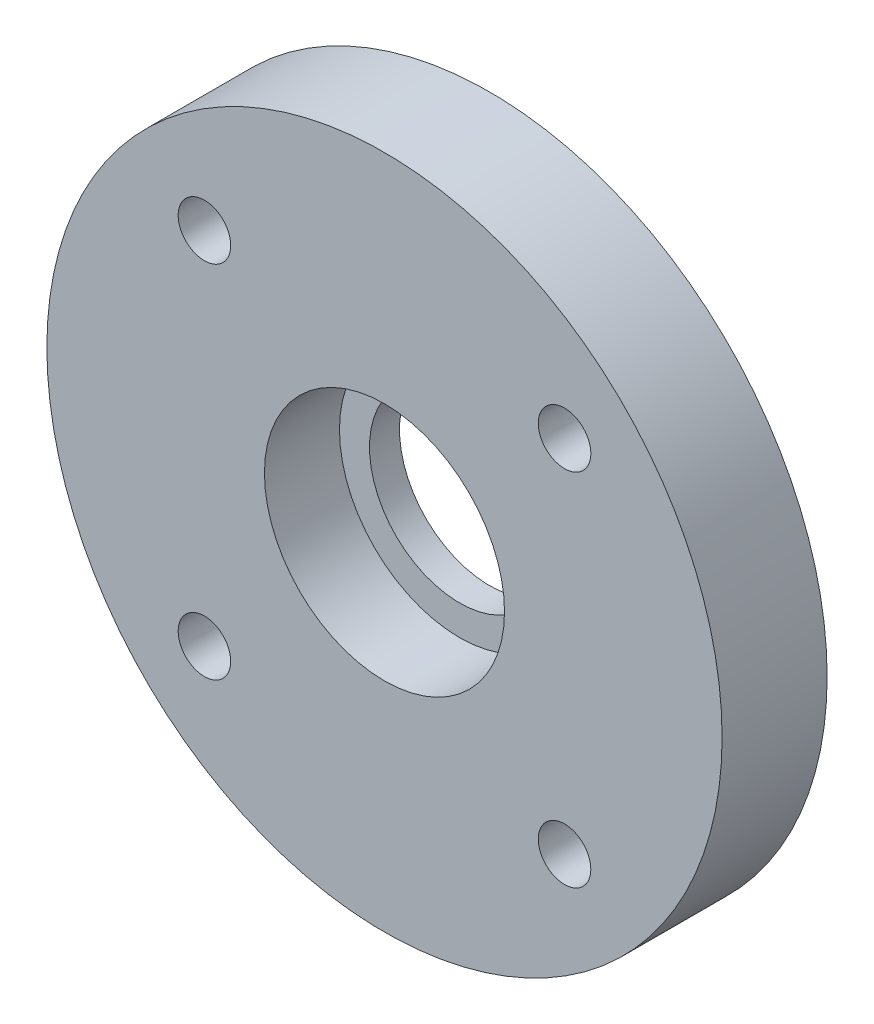
SolidWorks part; units mm, degrees
ref_plane "Front Plane" through (0, 0, 0) normal (0, 0, 1) x (1, 0, 0)
ref_plane "Top Plane" through (0, 0, 0) normal (0, 1, 0) x (1, 0, 0)
ref_plane "Right Plane" through (0, 0, 0) normal (1, 0, 0) x (0, 0, -1)
sketch "Sketch1" plane through (0, 0, 0) normal (0, 0, 1) x (1, 0, 0)
  circle A0 centre (0, 0) radius 22.5
  circle A1 centre (0, 0) radius 6
  dimension "D1" = 45
  dimension "D2" = 12
extrude "Boss-Extrude1" add sketch "Sketch1" along normal blind 7
sketch "Sketch2" plane through (0, 0, 7) normal (0, 0, 1) x (1, 0, 0)
  circle A0 centre (0, 0) radius 8
  dimension "D1" = 16
extrude "Cut-Extrude1" cut sketch "Sketch2" against normal blind 5
sketch "Sketch3" plane through (0, 0, 7) normal (0, 0, 1) x (1, 0, 0)
  line L0 (-3.5478, 0) -> (0, 0) construction
  line L1 (0, 0) -> (0, 3.9191) construction
  circle A0 centre (-12, 12) radius 1.75
  circle A1 centre (12, 12) radius 1.75
  circle A2 centre (12, -12) radius 1.75
  circle A3 centre (-12, -12) radius 1.75
  dimension "D1" = 3.5
  dimension "D2" = 12
  dimension "D3" = 12
extrude "Cut-Extrude2" cut sketch "Sketch3" against normal through all
